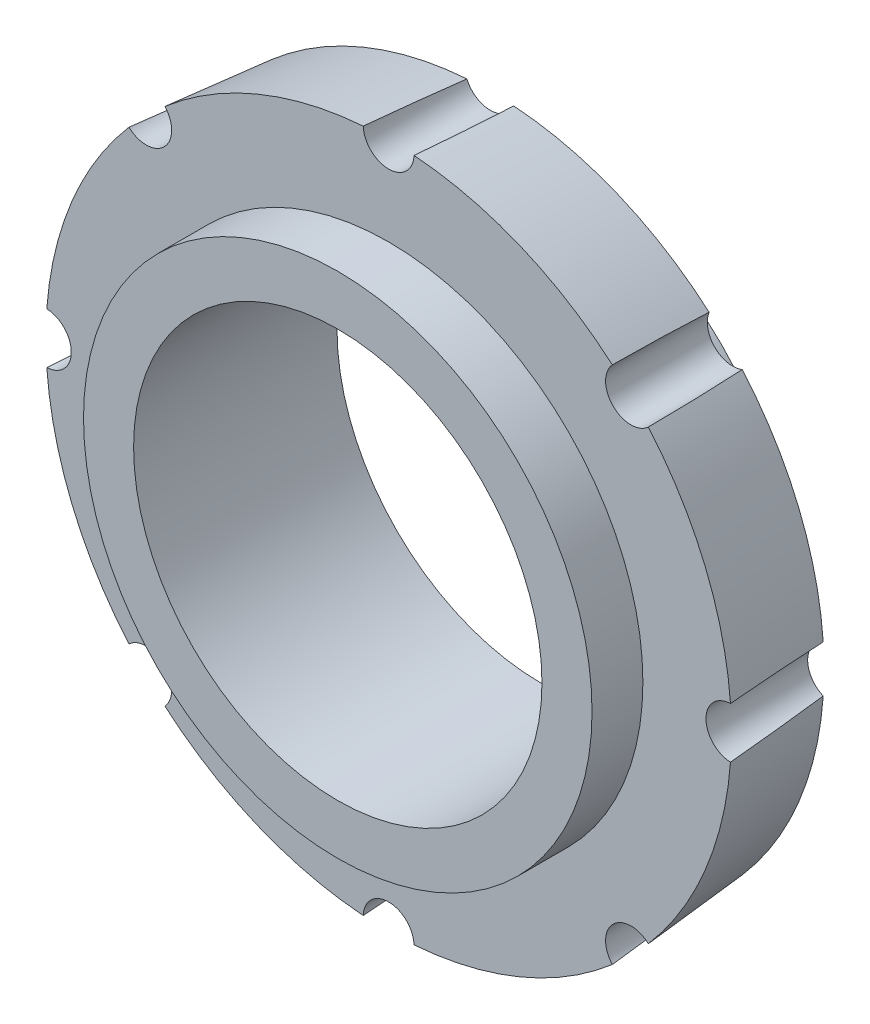
SolidWorks part; units mm, degrees
material "6063-T6"
ref_plane "Front Plane" through (0, 0, 0) normal (0, 0, 1) x (1, 0, 0)
ref_plane "Top Plane" through (0, 0, 0) normal (0, 1, 0) x (1, 0, 0)
ref_plane "Right Plane" through (0, 0, 0) normal (1, 0, 0) x (0, 0, -1)
sketch "Sketch1" plane through (0, 0, 0) normal (1, 0, 0) x (0, 0, -1)
  line L0 (0, 15.875) -> (0, 12.7483)
  line L1 (0, 15.875) -> (3.175, 15.875)
  line L2 (3.175, 15.875) -> (3.175, 21.4008)
  line L3 (3.175, 21.4008) -> (9.525, 20.8331)
  line L4 (9.525, 20.8331) -> (9.525, 15.875)
  line L5 (9.525, 15.875) -> (12.7, 15.875)
  line L6 (12.7, 15.875) -> (12.7, 12.7483)
  line L7 (0, 12.7483) -> (12.7, 12.7483)
  line L8 (0, 0) -> (10.4186, 0) construction
  dimension "D1" = 21.4008
  dimension "D2" = 20.8331
  dimension "D3" = 15.875
  dimension "D4" = 6.35
  dimension "D5" = 3.175
  dimension "D6" = 12.7
  dimension "D7" = 12.7483
revolve "Revolve1" add sketch "Sketch1" angle 360 about L8
sketch "Sketch2" plane through (0, 0, -3.175) normal (0, 0, 1) x (1, 0, 0)
  circle A0 centre (0, 21.4008) radius 1.5875
  circle A1 centre (0, 0) radius 21.4008 construction
extrude "Extrude1" cut sketch "Sketch2" against normal through all
pattern_circular "CirPattern1" count 8 every 45 about axis through (0, 0, 0) along (0, 0, 1) of "Extrude1"
